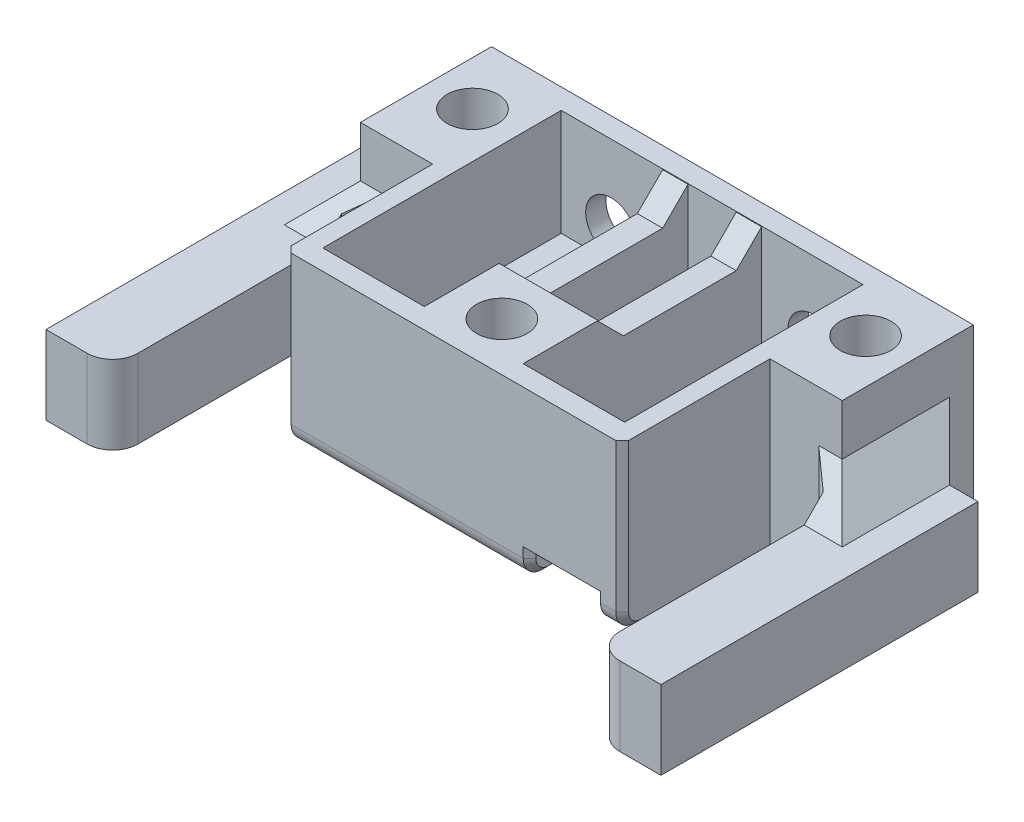
SolidWorks part; units mm, degrees
ref_plane "Front Plane" through (0, 0, 0) normal (0, 0, 1) x (1, 0, 0)
ref_plane "Top Plane" through (0, 0, 0) normal (0, 1, 0) x (1, 0, 0)
ref_plane "Right Plane" through (0, 0, 0) normal (1, 0, 0) x (0, 0, -1)
sketch "Sketch1" plane through (0, 0, 0) normal (0, 1, 0) x (1, 0, 0)
  line L1 (13.5, -11) -> (-13.5, -11)
  line L2 (13.5, -11) -> (13.5, 11)
  line L3 (13.5, 11) -> (-13.5, 11)
  line L4 (-13.5, -11) -> (-13.5, 11)
  line L5 (13.5, -11) -> (-13.5, 11) construction
  line L6 (13.5, 11) -> (-13.5, -11) construction
  point P0 (0, 0)
  dimension "D1" = 27
  dimension "D2" = 22
extrude "Boss-Extrude1" add sketch "Sketch1" along normal blind 12
shell "Shell1" thickness 1.6
sketch "Sketch2" plane through (0, 1.6, 0) normal (0, 1, 0) x (1, 0, 0)
  line L0 (-11.9, -9.4) -> (11.9, -9.4) construction
  line L4 (-3.9, 9.4) -> (-3.9, -9.4)
  line L5 (-1.9, 9.4) -> (-1.9, -9.4)
  line L6 (11.9, 9.4) -> (-11.9, 9.4) construction
  line L7 (-1.9, -9.4) -> (-3.9, -9.4)
  line L8 (-1.9, 9.4) -> (-3.9, 9.4)
  line L9 (-11.9, 9.4) -> (-11.9, -9.4) construction
  dimension "D1" = 8
  dimension "D2" = 2
extrude "Boss-Extrude2" add sketch "Sketch2" along normal up to surface (10.4 mm away) up to face at (0, 12, 0)
sketch "Sketch3" plane through (0, 12, 0) normal (0, 1, 0) x (1, 0, 0)
  line L0 (-11.9, -9.4) -> (-3.9, -9.4) construction
  line L1 (-11.9, -9.4) -> (-10.9, -9.4)
  line L2 (-11.9, -9.4) -> (-11.9, -11)
  line L3 (-11.9, -11) -> (-10.9, -11)
  line L4 (-10.9, -9.4) -> (-10.9, -11)
  line L5 (-13.5, -11) -> (13.5, -11) construction
  line L6 (-13.5, 11) -> (-13.5, -11) construction
  point P8 (-11.4, -11)
  dimension "D1" = 1
  dimension "D2" = 2.1
extrude "Cut-Extrude1" [suppressed] cut sketch "Sketch3" against normal blind 7.5
sketch "Sketch4" plane through (0, 0, -11) normal (0, 0, -1) x (-1, 0, 0)
  line L0 (16.436, 0) -> (-16.436, 0) construction
  circle A0 centre (7.9737, 6) radius 2
  dimension "D1" = 6
extrude "Cut-Extrude2" cut sketch "Sketch4" against normal blind 9
ref_plane "Mirror Plane" through (0, 0, 0) normal (-1, 0, 0) x (0, 0, 1)
sketch "Sketch6" plane through (-13.5, 0, 0) normal (-1, 0, 0) x (0, 0, 1)
  line L0 (-11, 12) -> (11, 12) construction
  line L1 (-0.66, 12) -> (-11, 12)
  line L2 (-0.66, 12) -> (-0.66, 0)
  line L3 (-0.66, 0) -> (-11, 0)
  line L4 (-11, 12) -> (-11, 0)
  dimension "D1" = 10.34
extrude "Boss-Extrude4" add sketch "Sketch6" along normal blind 5.5
sketch "Sketch7" plane through (-19, 0, 0) normal (-1, 0, 0) x (0, 0, 1)
  line L0 (-0.66, 12) -> (-11, 12) construction
  line L1 (-6.1164, 5) -> (18.8836, 5)
  line L2 (-6.1164, 5) -> (-6.1164, 0)
  line L3 (-6.1164, 0) -> (18.8836, 0)
  line L4 (18.8836, 5) -> (18.8836, 0)
  line L6 (-11, 0) -> (-0.66, 0) construction
  dimension "D1" = 25
  dimension "D3" = 7
extrude "Boss-Extrude5" add sketch "Sketch7" along normal blind 5.25
chamfer "Chamfer1" distance 3 angle 45 1 edges at (-19, 2.5, -6.1164)
sketch "Sketch8" plane through (0, 12, 0) normal (0, 1, 0) x (1, 0, 0)
  line L0 (13.5, 11) -> (-19, 11) construction
  line L1 (0, 6.413) -> (0, -6.413) construction
  circle A0 centre (-15.5, 6) radius 2
  dimension "D1" = 5
  dimension "D2" = 15.5
extrude "Cut-Extrude3" cut sketch "Sketch8" against normal through all
chamfer "Chamfer2" distance 1.5 angle 51 1 edges at (-19, 2.5, -0.66)
chamfer "Chamfer3" [suppressed] distance 2 angle 50
fillet "Fillet1" radius 2 1 edges at (-19, 2.5, 18.8836)
mirror "Mirror1" about plane through (0, 0, 0) normal (-1, 0, 0) of "Boss-Extrude2", "Cut-Extrude1", "Cut-Extrude2", "Boss-Extrude4", "Boss-Extrude5", "Chamfer1", "Cut-Extrude3", "Chamfer2", "Chamfer3", "Fillet1"
sketch "Sketch10" [suppressed] plane through (0, 1.6, 0) normal (0, 1, 0) x (1, 0, 0)
  line L0 (1.9, -9.4) -> (1.9, 9.4) construction
  line L1 (-1.9, -9.4) -> (1.9, -9.4)
  line L2 (-1.9, -9.4) -> (-1.9, -3.4)
  line L3 (-1.9, -3.4) -> (1.9, -3.4)
  line L4 (1.9, -9.4) -> (1.9, -3.4)
  dimension "D1" = 6
extrude "Boss-Extrude6" [suppressed] add sketch "Sketch10" along normal up to surface (10.4 mm away)
sketch "Sketch12" plane through (0, 0, 0) normal (0, -1, 0) x (1, 0, 0)
  line L0 (6.6, 11) -> (-13.5, 11)
  line L2 (6.6, -11) -> (6.6, 11)
  line L4 (11.1, -11) -> (11.1, 11)
  line L5 (11.1, -11) -> (19, -11)
  line L20 (24.25, 18.8836) -> (21, 18.8836)
  line L21 (19, 16.8836) -> (19, 0.84)
  line L22 (19, 0.84) -> (17.1477, -0.66)
  line L23 (17.1477, -0.66) -> (13.5, -0.66)
  line L24 (13.5, -0.66) -> (13.5, 11)
  line L25 (13.5, 11) -> (-13.5, 11)
  line L26 (-13.5, 11) -> (-13.5, -0.66)
  line L27 (-13.5, -0.66) -> (-17.1477, -0.66)
  line L28 (-17.1477, -0.66) -> (-19, 0.84)
  line L29 (-19, 0.84) -> (-19, 16.8836)
  line L30 (-21, 18.8836) -> (-24.25, 18.8836)
  line L31 (-24.25, 18.8836) -> (-24.25, -6.1164)
  line L32 (-24.25, -6.1164) -> (-22, -6.1164)
  line L33 (-22, -6.1164) -> (-19, -9.1164)
  line L34 (-19, -9.1164) -> (-19, -11)
  line L35 (-19, -11) -> (19, -11)
  line L36 (19, -11) -> (19, -9.1164)
  line L37 (19, -9.1164) -> (22, -6.1164)
  line L38 (22, -6.1164) -> (24.25, -6.1164)
  line L39 (24.25, -6.1164) -> (24.25, 18.8836)
  line L40 (24.25, 18.8836) -> (21, 18.8836)
  line L41 (19, 16.8836) -> (19, 0.84)
  line L42 (19, 0.84) -> (17.1477, -0.66)
  line L43 (17.1477, -0.66) -> (13.5, -0.66)
  line L44 (13.5, -0.66) -> (13.5, 11)
  line L45 (13.5, 11) -> (11.1, 11)
  line L46 (-13.5, 11) -> (-13.5, -0.66)
  line L47 (-13.5, -0.66) -> (-17.1477, -0.66)
  line L48 (-17.1477, -0.66) -> (-19, 0.84)
  line L49 (-19, 0.84) -> (-19, 16.8836)
  line L50 (-21, 18.8836) -> (-24.25, 18.8836)
  line L51 (-24.25, 18.8836) -> (-24.25, -6.1164)
  line L52 (-24.25, -6.1164) -> (-22, -6.1164)
  line L53 (-22, -6.1164) -> (-19, -9.1164)
  line L54 (-19, -9.1164) -> (-19, -11)
  line L55 (-19, -11) -> (6.6, -11)
  line L56 (19, -11) -> (19, -9.1164)
  line L57 (19, -9.1164) -> (22, -6.1164)
  line L58 (22, -6.1164) -> (24.25, -6.1164)
  line L59 (24.25, -6.1164) -> (24.25, 18.8836)
  arc A2 (21, 18.8836) -> (19, 16.8836) centre (21, 16.8836) ccw
  arc A3 (-19, 16.8836) -> (-21, 18.8836) centre (-21, 16.8836) ccw
  arc A4 (21, 18.8836) -> (19, 16.8836) centre (21, 16.8836) ccw
  arc A5 (-19, 16.8836) -> (-21, 18.8836) centre (-21, 16.8836) ccw
  dimension "D2" = 4.5
  dimension "D4" = 7.9
  dimension "D1" = 0
extrude "Boss-Extrude7" add sketch "Sketch12" along normal blind 1.2
sketch "Sketch13" plane through (0, 0, 0) normal (0, -1, 0) x (-1, 0, 0)
  line L1 (-6.6, -11) -> (-11.1, -11)
  line L2 (-6.6, -11) -> (-6.6, 11)
  line L3 (-6.6, 11) -> (-11.1, 11)
  line L4 (-11.1, -11) -> (-11.1, 11)
extrude "Cut-Extrude5" cut sketch "Sketch13" against normal blind 1
sketch "Sketch14" [suppressed] plane through (0, 12, 0) normal (0, 1, 0) x (1, 0, 0)
  line L1 (-1.9, 9.4) -> (1.9, 9.4)
  line L2 (-1.9, 9.4) -> (-1.9, -3.4)
  line L3 (-1.9, -3.4) -> (1.9, -3.4)
  line L4 (1.9, 9.4) -> (1.9, -3.4)
  line L21 (-13.5, -11) -> (13.5, -11)
  line L22 (13.5, -11) -> (13.5, 0.66)
  line L23 (13.5, 0.66) -> (19, 0.66)
  line L24 (19, 0.66) -> (19, 11)
  line L25 (19, 11) -> (-19, 11)
  line L26 (-19, 11) -> (-19, 0.66)
  line L27 (-19, 0.66) -> (-13.5, 0.66)
  line L28 (-13.5, 0.66) -> (-13.5, -11)
  line L41 (-13.5, -11) -> (13.5, -11)
  line L42 (13.5, -11) -> (13.5, 0.66)
  line L43 (13.5, 0.66) -> (19, 0.66)
  line L44 (19, 0.66) -> (19, 11)
  line L45 (19, 11) -> (-19, 11)
  line L46 (-19, 11) -> (-19, 0.66)
  line L47 (-19, 0.66) -> (-13.5, 0.66)
  line L48 (-13.5, 0.66) -> (-13.5, -11)
  circle A0 centre (-15.5, 6) radius 1.6
  circle A1 centre (15.5, 6) radius 1.6
  circle A2 centre (0, -7.1811) radius 1.6
  dimension "D1" = 0
sketch "Sketch16" [suppressed] plane through (13.5, 0, 0) normal (1, 0, 0) x (0, 0, -1)
  line L1 (0.66, -1.2) -> (-11, -1.2)
  line L2 (0.66, -1.2) -> (0.66, 12)
  line L3 (0.66, 12) -> (-11, 12)
  line L4 (-11, -1.2) -> (-11, 12)
sketch "Sketch17" plane through (-13.5, 0, 0) normal (-1, 0, 0) x (0, 0, 1)
  line L1 (-0.66, 12) -> (11, 12)
  line L2 (-0.66, 12) -> (-0.66, -1.2)
  line L3 (-0.66, -1.2) -> (11, -1.2)
  line L4 (11, 12) -> (11, -1.2)
extrude "Cut- tolerance fix" cut sketch "Sketch17" against normal blind 0.2
mirror "Mirror2" about plane through (0, 0, 0) normal (-1, 0, 0) of "Cut- tolerance fix"
fillet "Fillet2" radius 1.5 2 edges at (12.2, -1.2, 11) (-3.35, -1.2, 11)
sketch "Sketch18" plane through (0, 1.6, 0) normal (0, 1, 0) x (1, 0, 0)
  line L0 (-1.9, -9.4) -> (-1.9, 9.4) construction
  line L1 (1.9, -9.4) -> (-1.9, -9.4)
  line L2 (1.9, -9.4) -> (1.9, -3.5)
  line L3 (1.9, -3.5) -> (-1.9, -3.5)
  line L4 (-1.9, -9.4) -> (-1.9, -3.5)
  line L5 (-13.3, -11) -> (13.3, -11) construction
  dimension "D1" = 7.5
extrude "Boss-Extrude8" add sketch "Sketch18" along normal up to surface (10.4 mm away) up to face at (15.5, 12, -4)
sketch "Sketch11" plane through (0, 12, 0) normal (0, 1, 0) x (1, 0, 0)
  circle A0 centre (0, -7.1811) radius 2
extrude "Cut-Extrude6" cut sketch "Sketch11" against normal blind 10
sketch "Sketch19" plane through (0, 1.6, 0) normal (0, 1, 0) x (1, 0, 0)
  line L0 (3.9, 9.4) -> (3.9, -9.4) construction
  line L1 (3.9, -9.4) -> (11.9, -9.4) construction
  line L2 (11.9, -9.4) -> (11.9, 9.4) construction
  line L3 (11.9, 9.4) -> (3.9, 9.4) construction
  line L4 (-11.9, -9.4) -> (-3.9, -9.4) construction
  line L5 (-3.9, -9.4) -> (-3.9, 9.4) construction
  line L6 (-3.9, 9.4) -> (-11.9, 9.4) construction
  line L7 (-11.9, 9.4) -> (-11.9, -9.4) construction
  line L8 (3.9, 9.4) -> (3.9, -9.4)
  line L9 (3.9, -9.4) -> (11.9, -9.4)
  line L10 (11.9, -9.4) -> (11.9, 9.4)
  line L11 (11.9, 9.4) -> (3.9, 9.4)
  line L12 (-11.9, -9.4) -> (-3.9, -9.4)
  line L13 (-3.9, -9.4) -> (-3.9, 9.4)
  line L14 (-3.9, 9.4) -> (-11.9, 9.4)
  line L15 (-11.9, 9.4) -> (-11.9, -9.4)
extrude "Boss-Extrude9" add sketch "Sketch19" along normal blind 2
sketch "Sketch20" plane through (0, 1, 0) normal (0, -1, 0) x (1, 0, 0)
  line L4 (6.6, 11) -> (6.6, -11)
  line L5 (6.6, -11) -> (11.1, -11)
  line L6 (11.1, -11) -> (11.1, 11)
  line L7 (11.1, 11) -> (6.6, 11)
  line L8 (6.6, 11) -> (6.6, -11)
  line L9 (6.6, -11) -> (11.1, -11)
  line L10 (11.1, -11) -> (11.1, 11)
  line L11 (11.1, 11) -> (6.6, 11)
  dimension "D1" = 0
extrude "Cut-Extrude7" cut sketch "Sketch20" against normal blind 0.1
sketch "Sketch21" plane through (0, 12, 0) normal (0, 1, 0) x (1, 0, 0)
  line L0 (1.9, -3.5) -> (-1.9, -3.5) construction
  line L1 (3.9, -3.5) -> (-3.9, -3.5)
  line L2 (3.9, -3.5) -> (3.9, 9.4)
  line L3 (3.9, 9.4) -> (-3.9, 9.4)
  line L4 (-3.9, -3.5) -> (-3.9, 9.4)
  line L5 (3.9, -3.5) -> (-3.9, 9.4) construction
  line L6 (3.9, 9.4) -> (-3.9, -3.5) construction
  point P0 (0, 2.95)
extrude "Cut-Extrude8" cut sketch "Sketch21" against normal blind 2.05
chamfer "Chamfer4" distance 2 angle 45 4 edges at (2.9, 9.95, 3.5) (-2.9, 9.95, 3.5) (2.9, 9.95, -9.4) (-2.9, 9.95, -9.4)
chamfer "Chamfer5" distance 3 angle 45 4 edges at (-18.0738, 5, -0.66) (-19, 5, -4.8882) (18.0738, 5, -0.66) (19, 5, -4.8882)
sketch "Sketch22" plane through (6.6, 0, 0) normal (1, 0, 0) x (0, 0, -1)
  line L4 (-11, 1.1) -> (-11, 0.3)
  line L5 (-9.5, -1.2) -> (11, -1.2)
  line L6 (11, -1.2) -> (11, 1.1)
  line L7 (11, 1.1) -> (-11, 1.1)
  line L8 (-11, 1.1) -> (-11, 0.3)
  line L9 (-9.5, -1.2) -> (11, -1.2)
  line L10 (11, -1.2) -> (11, 1.1)
  line L11 (11, 1.1) -> (-11, 1.1)
  arc A1 (-11, 0.3) -> (-9.5, -1.2) centre (-9.5, 0.3) ccw
  arc A2 (-11, 0.3) -> (-9.5, -1.2) centre (-9.5, 0.3) ccw
  dimension "D1" = 0
extrude "tolerance adj" cut sketch "Sketch22" against normal blind 0.6
chamfer "Chamfer6" distance 0.5 angle 45 12 edges at (-13.3, 6.15, 11) (-13.3, -0.7607, 10.5607) (-13.3, -1.2, 4.42) (13.3, 6.15, 11) (13.3, -0.7607, 10.5607) (13.3, -1.2, 4.42) (6, -1.2, -0.75) (6, -0.7607, 10.5607) (6, 0.7, 11) (11.1, 0.7, 11) (11.1, -0.7607, 10.5607) (11.1, -1.2, -0.75)
